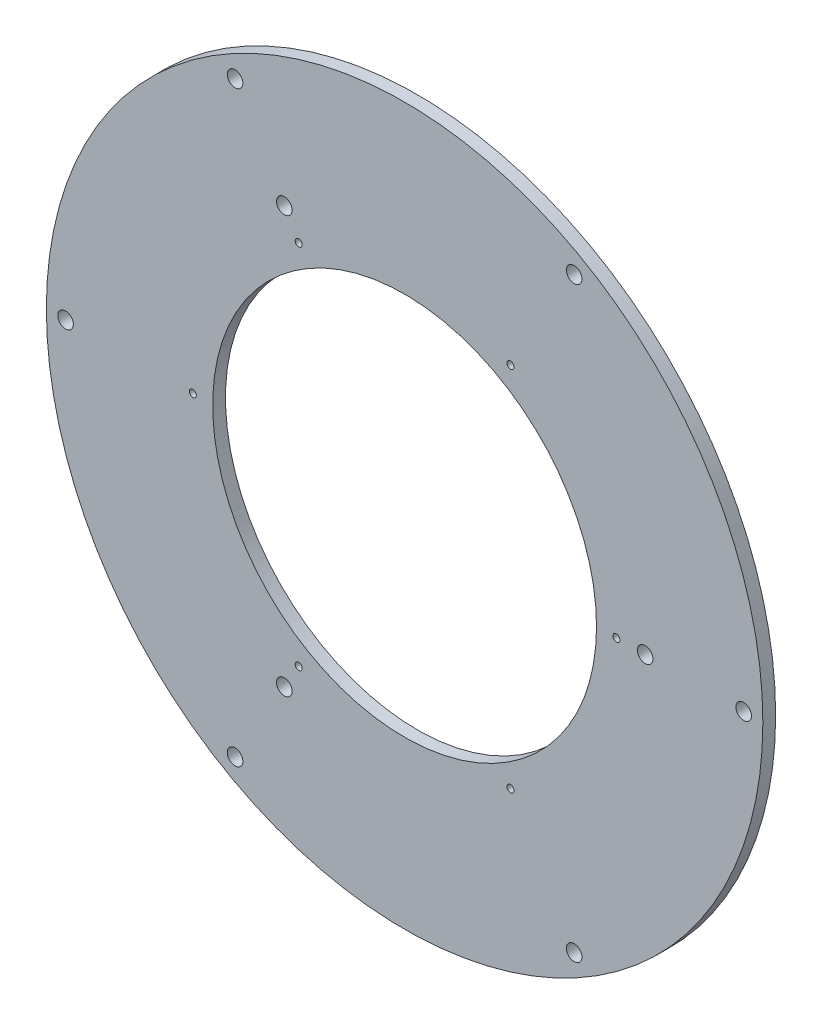
SolidWorks part; units mm, degrees
ref_plane "Спереди" through (0, 0, 0) normal (0, 0, 1) x (1, 0, 0)
ref_plane "Сверху" through (0, 0, 0) normal (0, 1, 0) x (1, 0, 0)
ref_plane "Справа" through (0, 0, 0) normal (1, 0, 0) x (0, 0, -1)
sketch "Эскиз2" plane through (0, 0, 0) normal (0, 0, 1) x (-1, 0, 0)
  line L0 (-150, 0) -> (-165.5, 0) construction
  line L1 (-165.5, 0) -> (-188, 0) construction
  line L2 (-188, 0) -> (-280, 0) construction
  circle A0 centre (0, 0) radius 150
  circle A1 centre (0, 0) radius 280
  circle A6 centre (-188, 0) radius 6.1
  circle A7 centre (-165.5, 0) radius 2.75
  circle A8 centre (-265, 0) radius 6.1
  circle A9 centre (-82.75, 143.3272) radius 2.75
  circle A10 centre (82.75, 143.3272) radius 2.75
  circle A11 centre (165.5, 0) radius 2.75
  circle A12 centre (82.75, -143.3272) radius 2.75
  circle A13 centre (-82.75, -143.3272) radius 2.75
  circle A14 centre (94, 162.8128) radius 6.1
  circle A15 centre (94, -162.8128) radius 6.1
  circle A16 centre (-132.5, 229.4967) radius 6.1
  circle A17 centre (132.5, 229.4967) radius 6.1
  circle A18 centre (265, 0) radius 6.1
  circle A19 centre (132.5, -229.4967) radius 6.1
  circle A20 centre (-132.5, -229.4967) radius 6.1
  point P28 (0, 0)
  point P32 (0, 0)
  point P43 (0, 0)
  dimension "D1" = 300
  dimension "D2" = 560
  dimension "D3" = 12.2
  dimension "D7" = 12.2
  dimension "D8" = 5.5
  dimension "D4" = 15
  dimension "D5" = 15.5
  dimension "D6" = 22.5
  dimension "D9" = 6
  dimension "D10" = 3
  dimension "D11" = 6
extrude "Бобышка-Вытянуть1" add sketch "Эскиз2" along normal blind 10
